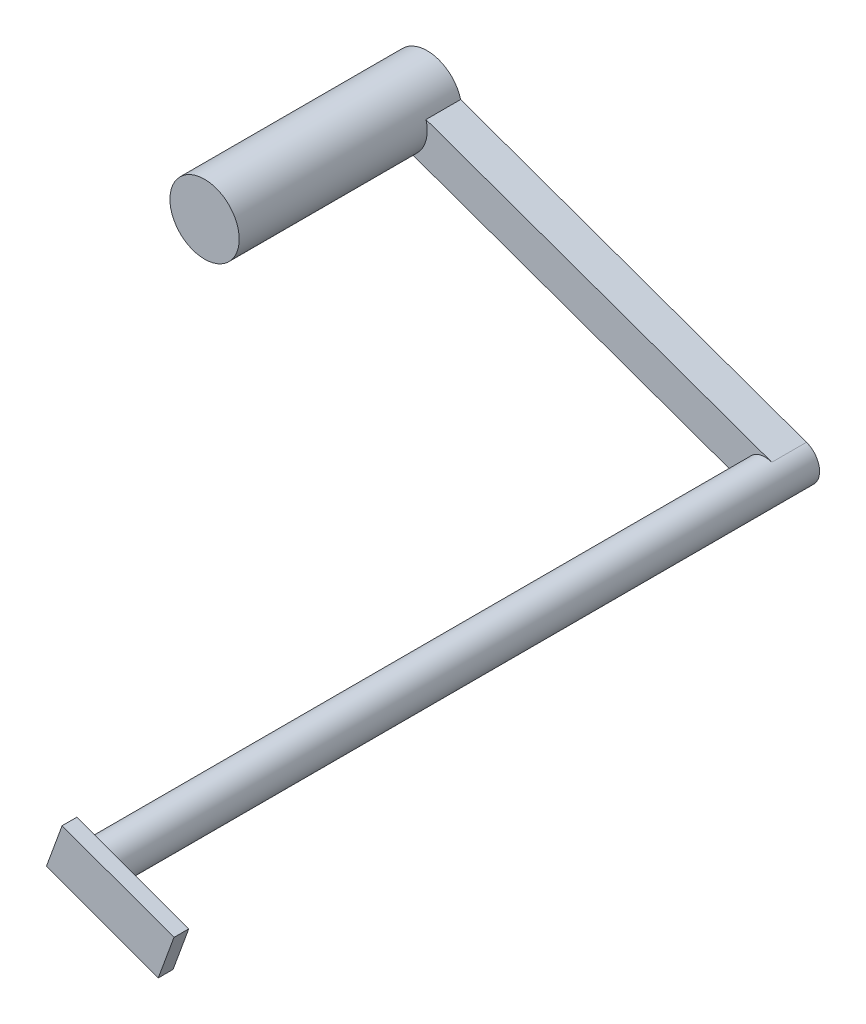
SolidWorks part; units mm, degrees
ref_plane "前视基准面" through (0, 0, 0) normal (0, 0, 1) x (1, 0, 0)
ref_plane "上视基准面" through (0, 0, 0) normal (0, 1, 0) x (1, 0, 0)
ref_plane "右视基准面" through (0, 0, 0) normal (1, 0, 0) x (0, 0, -1)
other "Configuration Table"
sketch "草图1" plane through (0, 0, 0) normal (0, 0, 1) x (1, 0, 0)
  circle A0 centre (-86.6066, -63.7835) radius 7
extrude "凸台-拉伸1" add sketch "草图1" along normal blind 45
sketch "草图3" plane through (0, 0, 0) normal (0, 0, -1) x (-1, 0, 0)
  line L0 (86.6066, -63.7835) -> (11.2929, -90.7622) construction
  line L1 (87.9556, -67.5492) -> (12.6419, -94.5278)
  line L2 (85.2577, -60.0178) -> (9.944, -86.9965)
  arc A0 (87.9556, -67.5492) -> (85.2577, -60.0178) centre (86.6066, -63.7835) ccw
  arc A1 (9.944, -86.9965) -> (12.6419, -94.5278) centre (11.2929, -90.7622) ccw
  point P2 (48.9498, -77.2728)
extrude "凸台-拉伸2" add sketch "草图3" against normal blind 7
sketch "草图7" plane through (0, 0, 7) normal (0, 0, 1) x (1, 0, 0)
  circle A3 centre (-11.2929, -90.7622) radius 4
extrude "凸台-拉伸3" add sketch "草图7" along normal blind 135
sketch "草图8" plane through (0, 0, 142) normal (0, 0, 1) x (1, 0, 0)
  line L0 (-85.2459, -60.0221) -> (-19.7506, -83.9496) construction
  line L1 (-79.8497, -61.9551) -> (-9.944, -86.9965) construction
  line L2 (2.7174, -96.4164) -> (8.6404, -80.2036) construction
  line L3 (2.8901, -95.9437) -> (-11.2929, -90.7622) construction
  line L4 (-15.3941, -84.336) -> (7.2076, -92.5931)
  line L5 (7.2076, -92.5931) -> (4.0309, -101.2883)
  line L7 (4.0309, -101.2883) -> (-18.5708, -93.0312)
  line L8 (-18.5708, -93.0312) -> (-15.3941, -84.336)
extrude "凸台-拉伸4" add sketch "草图8" along normal blind 3
